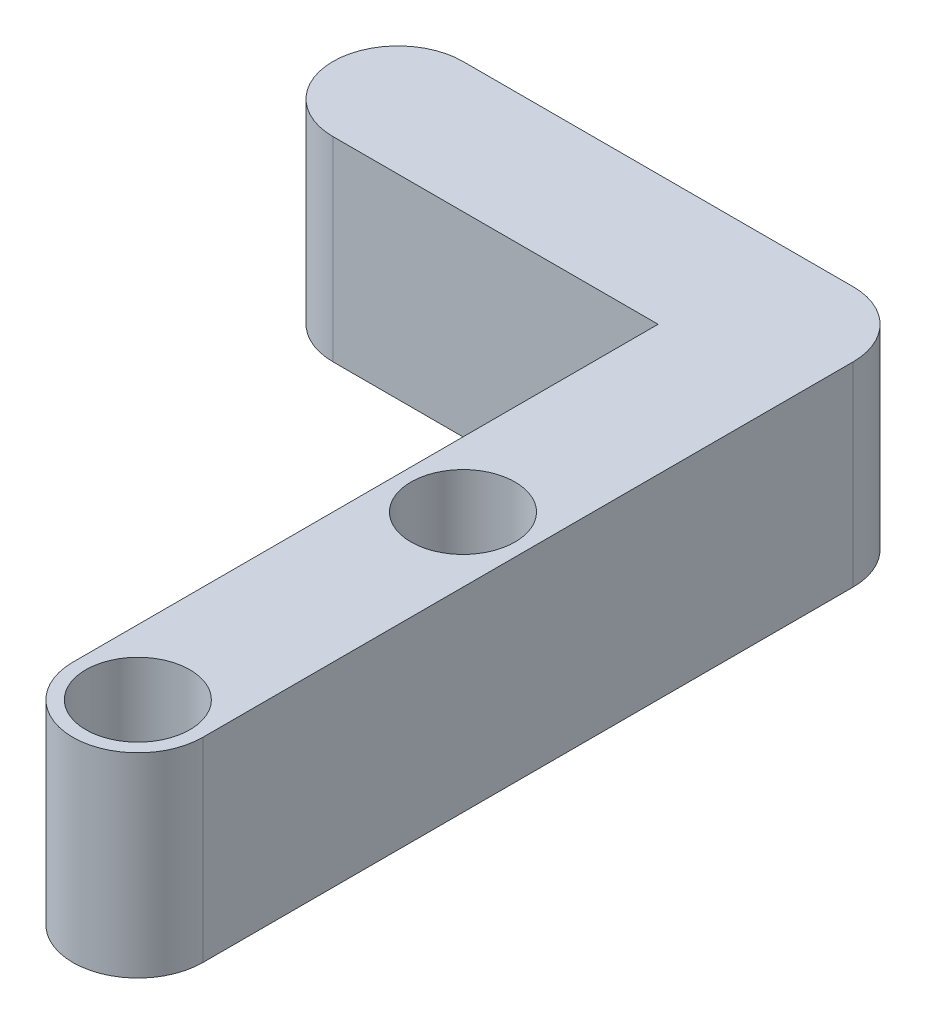
SolidWorks part; units mm, degrees
ref_plane "Front Plane" through (0, 0, 0) normal (0, 0, 1) x (1, 0, 0)
ref_plane "Top Plane" through (0, 0, 0) normal (0, 1, 0) x (1, 0, 0)
ref_plane "Right Plane" through (0, 0, 0) normal (1, 0, 0) x (0, 0, -1)
sketch "Sketch1" plane through (0, 0, 0) normal (0, 1, 0) x (1, 0, 0)
  line L0 (-38.6229, -14.8636) -> (-38.6229, -19.3636) construction
  line L1 (-38.1229, -14.8636) -> (-38.1229, -19.3636)
  line L2 (-39.1229, -15.3636) -> (-39.1229, -19.3636)
  line L3 (-38.6229, -19.3636) -> (-38.6229, -14.3636) construction
  line L6 (-38.6229, -16.8636) -> (-38.6229, -18.3636)
  line L7 (-38.6229, -16.8636) -> (-38.6229, -15.3636)
  line L8 (-38.6229, -15.3636) -> (-34.6229, -15.3636) construction
  line L9 (-38.6229, -14.8636) -> (-34.6229, -14.8636)
  line L10 (-38.6229, -15.8636) -> (-34.6229, -15.8636)
  line L11 (-34.6229, -15.3636) -> (-34.5657, -13.3644) construction
  line L12 (-35.1227, -15.3493) -> (-35.0655, -13.3501)
  line L13 (-34.1232, -15.3779) -> (-34.0659, -13.3787)
  line L14 (-34.5657, -13.3644) -> (-36.0657, -13.3644) construction
  line L15 (-34.5657, -13.8644) -> (-36.0657, -13.8644)
  line L16 (-34.5657, -12.8644) -> (-36.0657, -12.8644)
  line L17 (-39.1229, -19.3636) -> (-39.1229, -14.3636)
  line L18 (-38.1229, -19.3636) -> (-38.1229, -14.3636)
  line L19 (-38.6229, -14.3636) -> (-41.6229, -14.3636) construction
  line L20 (-38.6229, -14.8636) -> (-41.6229, -14.8636)
  line L21 (-38.6229, -13.8636) -> (-41.6229, -13.8636)
  arc A1 (-39.1229, -19.3636) -> (-38.1229, -19.3636) centre (-38.6229, -19.3636) ccw
  circle A5 centre (-38.6229, -19.3636) radius 0.4
  circle A6 centre (-38.6229, -16.8636) radius 0.4
  arc A7 (-38.6229, -14.8636) -> (-38.6229, -15.8636) centre (-38.6229, -15.3636) ccw
  arc A8 (-34.6229, -15.8636) -> (-34.6229, -14.8636) centre (-34.6229, -15.3636) ccw
  arc A9 (-35.1227, -15.3493) -> (-34.1232, -15.3779) centre (-34.6229, -15.3636) ccw
  arc A10 (-34.0659, -13.3787) -> (-35.0655, -13.3501) centre (-34.5657, -13.3644) ccw
  arc A11 (-34.5657, -13.8644) -> (-34.5657, -12.8644) centre (-34.5657, -13.3644) ccw
  arc A12 (-36.0657, -12.8644) -> (-36.0657, -13.8644) centre (-36.0657, -13.3644) ccw
  arc A13 (-39.1229, -19.3636) -> (-38.1229, -19.3636) centre (-38.6229, -19.3636) ccw
  arc A14 (-38.1229, -14.3636) -> (-39.1229, -14.3636) centre (-38.6229, -14.3636) ccw
  arc A15 (-38.6229, -14.8636) -> (-38.6229, -13.8636) centre (-38.6229, -14.3636) ccw
  arc A16 (-41.6229, -13.8636) -> (-41.6229, -14.8636) centre (-41.6229, -14.3636) ccw
  point P0 (-38.6229, -16.8636)
  point P2 (-38.8078, -16.863)
  point P19 (-36.6229, -15.3636)
  point P28 (-34.5943, -14.364)
  point P33 (-35.3157, -13.3644)
  point P41 (-40.1229, -14.3636)
extrude "Boss-Extrude1" add sketch "Sketch1" along normal blind 1.5
